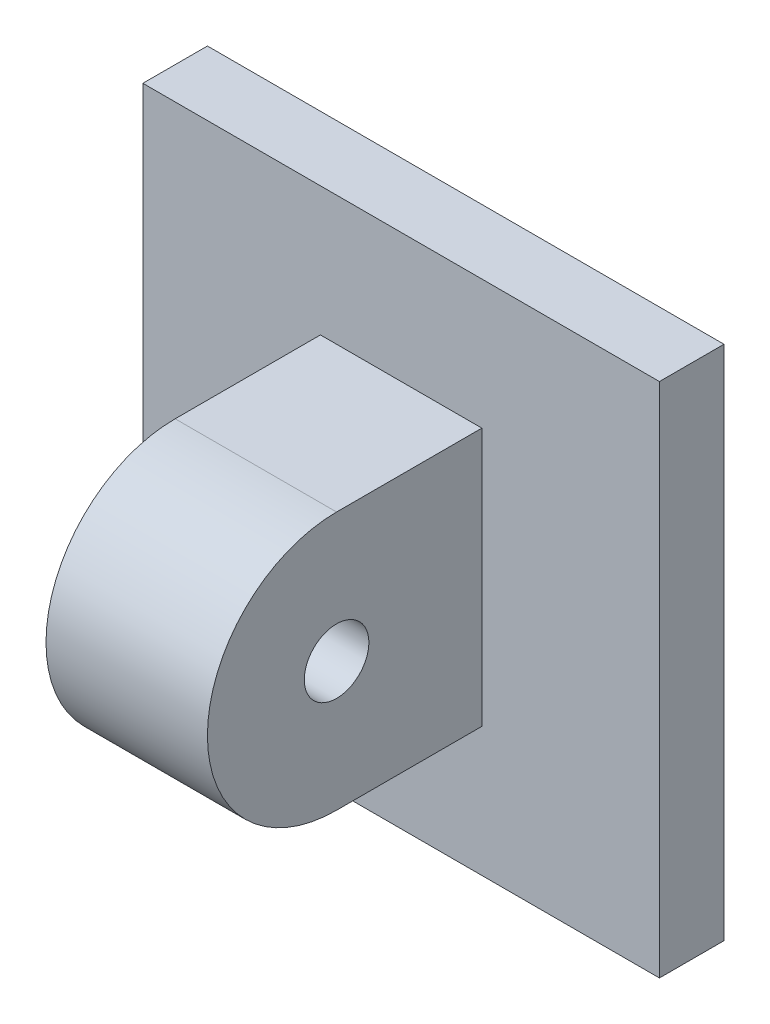
SolidWorks part; units mm, degrees
ref_plane "前视基准面" through (0, 0, 0) normal (0, 0, 1) x (1, 0, 0)
ref_plane "上视基准面" through (0, 0, 0) normal (0, 1, 0) x (1, 0, 0)
ref_plane "右视基准面" through (0, 0, 0) normal (1, 0, 0) x (0, 0, -1)
sketch "草图1" plane through (0, 0, 0) normal (0, 0, 1) x (1, 0, 0)
  line L1 (0, 0) -> (16, 0)
  line L2 (0, 0) -> (0, 16)
  line L3 (0, 16) -> (16, 16)
  line L4 (16, 0) -> (16, 16)
extrude "凸台-拉伸1" add sketch "草图1" along normal blind 2
sketch "草图2" plane through (0, 0, 2) normal (0, 0, 1) x (1, 0, 0)
  line L1 (5.5, 12) -> (10.5, 12)
  line L2 (5.5, 12) -> (5.5, 4)
  line L3 (5.5, 4) -> (10.5, 4)
  line L4 (10.5, 12) -> (10.5, 4)
  point P4 (0, 0)
  point P5 (0, 0)
  point P6 (0, 0)
extrude "凸台-拉伸2" add sketch "草图2" along normal blind 4.5
sketch "草图3" plane through (5.5, 0, 0) normal (-1, 0, 0) x (0, 0, 1)
  line L0 (6.5, 12) -> (6.5, 4) construction
  circle A0 centre (6.5, 8) radius 4
extrude "凸台-拉伸3" add sketch "草图3" against normal blind 5
sketch "草图4" plane through (5.5, 0, 0) normal (-1, 0, 0) x (0, 0, 1)
  circle A1 centre (6.5, 8) radius 1
sketch "草图5" plane through (5.5, 0, 0) normal (-1, 0, 0) x (0, 0, 1)
extrude "切除-拉伸1" cut sketch "草图4" against normal blind 10
